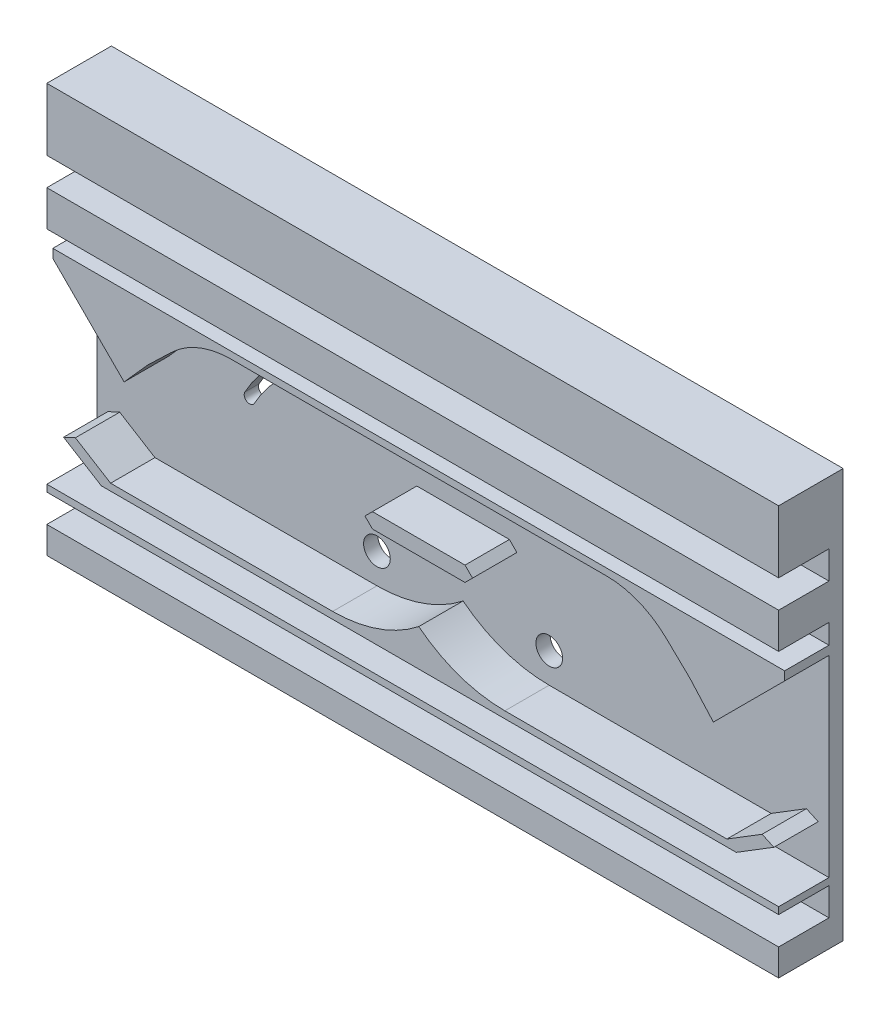
SolidWorks part; units mm, degrees
ref_plane "Front Plane" through (0, 0, 0) normal (0, 0, 1) x (1, 0, 0)
ref_plane "Top Plane" through (0, 0, 0) normal (0, 1, 0) x (1, 0, 0)
ref_plane "Right Plane" through (0, 0, 0) normal (1, 0, 0) x (0, 0, -1)
sketch "Sketch1" plane through (0, 0, 0) normal (0, 0, 1) x (1, 0, 0)
  line L0 (381, 92.3925) -> (367.3475, 92.3925)
  line L1 (381, 110.49) -> (325.6172, 110.49)
  line L2 (279.6982, 67.437) -> (290.0904, 61.0235)
  line L3 (365.125, 90.17) -> (367.3475, 92.3925)
  line L4 (365.125, 90.17) -> (367.3475, 87.9475)
  line L5 (294.0823, 88.9) -> (273.05, 109.9323)
  line L6 (287.3375, 58.9915) -> (276.225, 65.8495)
  line L7 (276.225, 65.8495) -> (279.6982, 67.437)
  line L8 (300.99, 96.647) -> (294.0823, 88.9)
  line L9 (300.99, 96.647) -> (308.0122, 103.3992)
  line L10 (301.3075, 46.99) -> (300.7868, 46.99)
  line L11 (488.95, 34.925) -> (488.95, 155.575)
  line L12 (381, 34.925) -> (488.95, 34.925)
  line L13 (381, 42.8625) -> (488.95, 42.8625)
  line L14 (482.3018, 67.437) -> (471.9096, 61.0235)
  line L15 (396.875, 90.17) -> (394.6525, 92.3925)
  line L16 (396.875, 90.17) -> (394.6525, 87.9475)
  line L17 (467.9177, 88.9) -> (488.95, 109.9323)
  line L18 (273.05, 155.575) -> (381, 155.575)
  line L19 (381, 34.925) -> (273.05, 34.925)
  line L20 (273.05, 34.925) -> (273.05, 155.575)
  line L21 (381, 42.8625) -> (273.05, 42.8625)
  line L22 (273.05, 51.1175) -> (381, 51.1175)
  line L23 (381, 137.16) -> (273.05, 137.16)
  line L24 (273.05, 128.905) -> (381, 128.905)
  line L25 (287.3375, 58.9915) -> (381, 58.9915)
  line L26 (290.0904, 61.0235) -> (355.6, 61.0235)
  line L27 (367.3475, 87.9475) -> (381, 87.9475)
  line L28 (365.125, 90.17) -> (367.3475, 87.9475)
  line L29 (367.3475, 92.3925) -> (365.125, 90.17)
  line L30 (488.95, 118.364) -> (273.05, 118.364)
  line L31 (488.95, 112.522) -> (273.05, 112.522)
  line L32 (474.6625, 58.9915) -> (485.775, 65.8495)
  line L33 (485.775, 65.8495) -> (482.3018, 67.437)
  line L34 (461.01, 96.647) -> (467.9177, 88.9)
  line L35 (461.01, 96.647) -> (453.9878, 103.3992)
  line L36 (488.95, 155.575) -> (381, 155.575)
  line L37 (488.95, 51.1175) -> (381, 51.1175)
  line L38 (381, 137.16) -> (488.95, 137.16)
  line L39 (488.95, 128.905) -> (381, 128.905)
  line L40 (474.6625, 58.9915) -> (381, 58.9915)
  line L41 (471.9096, 61.0235) -> (406.4, 61.0235)
  line L42 (394.6525, 87.9475) -> (381, 87.9475)
  line L43 (396.875, 90.17) -> (394.6525, 87.9475)
  line L44 (394.6525, 92.3925) -> (396.875, 90.17)
  line L45 (381, 92.3925) -> (394.6525, 92.3925)
  line L46 (381, 110.49) -> (436.3828, 110.49)
  line L47 (460.6925, 46.99) -> (461.2132, 46.99)
  arc A0 (355.6, 61.0235) -> (381, 69.85) centre (355.6, 101.9835) ccw
  arc A1 (325.6172, 110.49) -> (308.0122, 103.3992) centre (325.6172, 85.09) ccw
  circle A2 centre (381, 46.99) radius 1.1303
  circle A3 centre (301.0471, 46.99) radius 1.1303
  circle A4 centre (460.9528, 46.99) radius 1.1303
  circle A5 centre (355.5825, 69.8475) radius 3.937
  arc A6 (316.6215, 91.064) -> (319.4098, 89.5456) centre (318.0156, 90.3048) ccw
  arc A7 (326.2581, 98.7555) -> (323.852, 100.8152) centre (325.1295, 99.8722) ccw
  arc A8 (323.852, 100.8152) -> (316.6215, 91.064) centre (354.9876, 70.1715) ccw
  arc A9 (326.2581, 98.7555) -> (319.4098, 89.5456) centre (355.3412, 69.9789) ccw
  arc A10 (381, 69.85) -> (406.4, 61.0235) centre (406.4, 101.9835) ccw
  arc A11 (453.9878, 103.3992) -> (436.3828, 110.49) centre (436.3828, 85.09) ccw
  circle A12 centre (406.4175, 69.8475) radius 3.937
  arc A13 (442.5902, 89.5456) -> (445.3785, 91.064) centre (443.9844, 90.3048) ccw
  arc A14 (438.148, 100.8152) -> (435.7419, 98.7555) centre (436.8705, 99.8722) ccw
  arc A15 (445.3785, 91.064) -> (438.148, 100.8152) centre (407.0124, 70.1715) ccw
  arc A16 (442.5902, 89.5456) -> (435.7419, 98.7555) centre (406.6588, 69.9789) ccw
sketch "Sketch3" plane through (0, 0, 0) normal (0, 0, 1) x (1, 0, 0)
  line L1 (273.05, 155.575) -> (488.95, 155.575)
  line L2 (273.05, 155.575) -> (273.05, 34.925)
  line L3 (273.05, 34.925) -> (488.95, 34.925)
  line L4 (488.95, 155.575) -> (488.95, 34.925)
extrude "Extrude1" add sketch "Sketch3" along normal blind 4.191
sketch "Sketch4" plane through (0, 0, 0) normal (0, 0, 1) x (1, 0, 0)
  line L0 (488.95, 34.925) -> (488.95, 155.575) construction
  line L1 (273.05, 155.575) -> (488.95, 155.575)
  line L2 (273.05, 155.575) -> (273.05, 137.16)
  line L3 (273.05, 137.16) -> (488.95, 137.16)
  line L4 (488.95, 155.575) -> (488.95, 137.16)
  line L5 (273.05, 128.905) -> (488.95, 128.905)
  line L6 (273.05, 128.905) -> (273.05, 118.364)
  line L7 (273.05, 118.364) -> (488.95, 118.364)
  line L8 (488.95, 128.905) -> (488.95, 118.364)
  line L9 (273.05, 34.925) -> (488.95, 34.925)
  line L10 (273.05, 34.925) -> (273.05, 42.8625)
  line L11 (273.05, 42.8625) -> (488.95, 42.8625)
  line L12 (488.95, 34.925) -> (488.95, 42.8625)
  line L13 (273.05, 51.1175) -> (488.95, 51.1175)
  line L14 (273.05, 51.1175) -> (273.05, 53.1495)
  line L15 (273.05, 53.1495) -> (488.95, 53.1495)
  line L16 (488.95, 51.1175) -> (488.95, 53.1495)
extrude "Extrude2" add sketch "Sketch4" along normal blind 19.05
sketch "Sketch5" plane through (0, 0, 0) normal (0, 0, 1) x (1, 0, 0)
  line L0 (381, 58.9915) -> (287.3375, 58.9915)
  line L1 (287.3375, 58.9915) -> (276.225, 65.8495)
  line L2 (287.3375, 58.9915) -> (276.225, 65.8495) construction
  line L3 (279.6982, 67.437) -> (276.225, 65.8495)
  line L4 (279.6982, 67.437) -> (290.0904, 61.0235)
  line L5 (290.0904, 61.0235) -> (355.6, 61.0235)
  line L6 (381, 58.9915) -> (474.6625, 58.9915)
  line L7 (474.6625, 58.9915) -> (485.775, 65.8495)
  line L8 (485.775, 65.8495) -> (482.3018, 67.437)
  line L9 (482.3018, 67.437) -> (471.9096, 61.0235)
  line L10 (471.9096, 61.0235) -> (406.4, 61.0235)
  line L11 (381, 87.9475) -> (367.3475, 87.9475)
  line L12 (367.3475, 87.9475) -> (365.125, 90.17)
  line L13 (365.125, 90.17) -> (367.3475, 92.3925)
  line L14 (367.3475, 92.3925) -> (381, 92.3925)
  line L15 (381, 92.3925) -> (394.6525, 92.3925)
  line L16 (394.6525, 92.3925) -> (396.875, 90.17)
  line L17 (396.875, 90.17) -> (394.6525, 87.9475)
  line L18 (394.6525, 87.9475) -> (381, 87.9475)
  line L19 (436.3828, 110.49) -> (325.6172, 110.49)
  line L20 (308.0122, 103.3992) -> (300.99, 96.647)
  line L21 (300.99, 96.647) -> (294.0823, 88.9)
  line L22 (294.0823, 88.9) -> (273.05, 109.9323)
  line L23 (273.05, 109.9323) -> (273.05, 112.522)
  line L24 (273.05, 112.522) -> (488.95, 112.522)
  line L25 (488.95, 112.522) -> (488.95, 109.9323)
  line L26 (488.95, 109.9323) -> (467.9177, 88.9)
  line L27 (467.9177, 88.9) -> (461.01, 96.647)
  line L28 (461.01, 96.647) -> (453.9878, 103.3992)
  arc A0 (355.6, 61.0235) -> (381, 69.85) centre (355.6, 101.9835) ccw
  arc A1 (406.4, 61.0235) -> (381, 69.85) centre (406.4, 101.9835) cw
  arc A2 (325.6172, 110.49) -> (308.0122, 103.3992) centre (325.6172, 85.09) ccw
  arc A3 (453.9878, 103.3992) -> (436.3828, 110.49) centre (436.3828, 85.09) ccw
extrude "Extrude3" add sketch "Sketch5" along normal blind 17.272
sketch "Sketch8" plane through (0, 0, 0) normal (0, 0, 1) x (1, 0, 0)
  arc A0 (319.4098, 89.5456) -> (326.2581, 98.7555) centre (355.3412, 69.9789) cw
  arc A3 (316.6215, 91.064) -> (323.852, 100.8152) centre (354.9876, 70.1715) cw
  arc A4 (323.852, 100.8152) -> (326.2581, 98.7555) centre (325.1295, 99.8722) cw
  arc A5 (319.4098, 89.5456) -> (316.6215, 91.064) centre (318.0156, 90.3048) cw
  arc A6 (438.148, 100.8152) -> (445.3785, 91.064) centre (407.0124, 70.1715) cw
  arc A7 (435.7419, 98.7555) -> (442.5902, 89.5456) centre (406.6588, 69.9789) cw
  arc A8 (445.3785, 91.064) -> (442.5902, 89.5456) centre (443.9844, 90.3048) cw
  arc A9 (435.7419, 98.7555) -> (438.148, 100.8152) centre (436.8705, 99.8722) cw
  circle A10 centre (355.5825, 69.8475) radius 3.937
  circle A11 centre (406.4175, 69.8475) radius 3.937
  circle A12 centre (381, 46.99) radius 1.1303
  circle A13 centre (460.9528, 46.99) radius 1.1303
  circle A14 centre (301.0471, 46.99) radius 1.1303
extrude "Cut-Extrude1" cut sketch "Sketch8" along normal up to surface (19.05 mm away) up to face at (381, 146.3675, 19.05)
